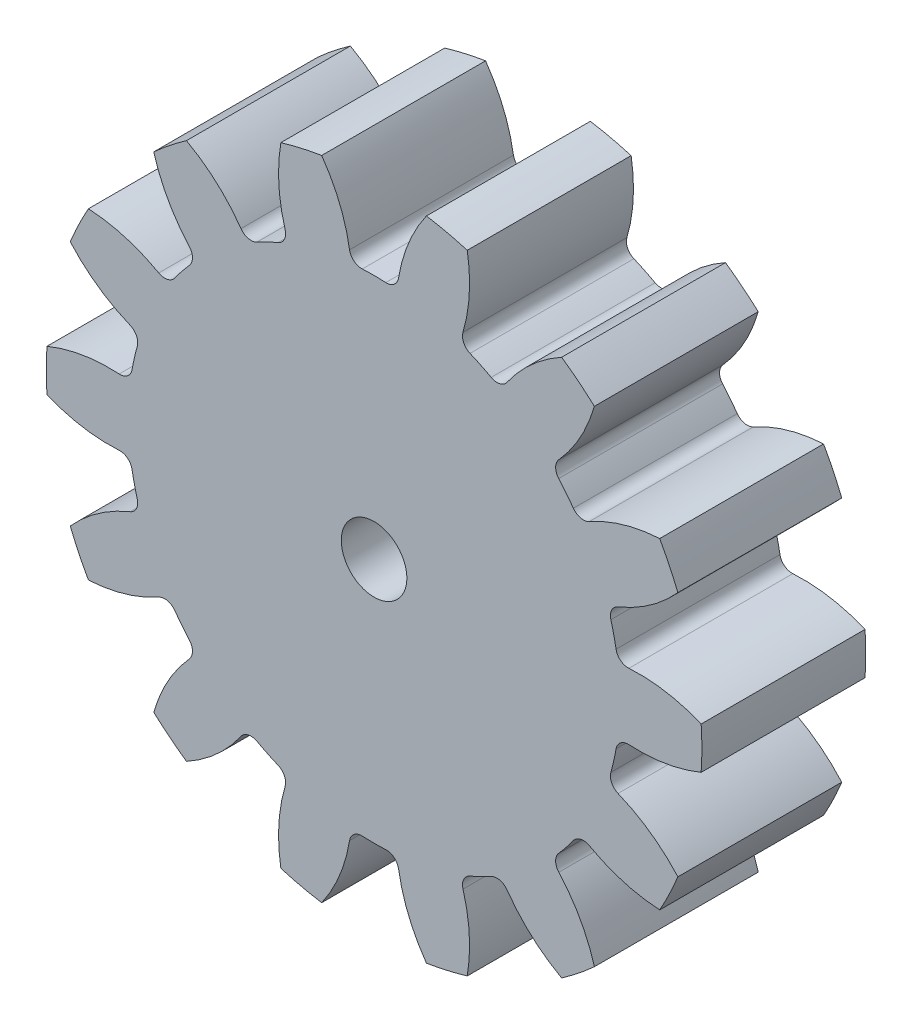
SolidWorks part; units mm, degrees
ref_plane "Front" through (0, 0, 0) normal (0, 0, 1) x (1, 0, 0)
ref_plane "Top" through (0, 0, 0) normal (0, 1, 0) x (1, 0, 0)
ref_plane "Right" through (0, 0, 0) normal (1, 0, 0) x (0, 0, -1)
sketch "Sketch1" plane through (0, 0, 0) normal (0, 0, 1) x (1, 0, 0)
  circle A0 centre (0, 0) radius 7.5
  circle A1 centre (0, 0) radius 10
  circle A2 centre (0, 0) radius 8.75
  dimension "D1" = 20
  dimension "D2" = 15
  dimension "D3" = 17.5
extrude "Boss-Extrude1" add sketch "Sketch1" along normal mid plane 5 contours A1
sketch "Sketch3" plane through (0, 0, 0) normal (0, 0, 1) x (1, 0, 0)
  line L0 (0, 0) -> (0, 10) construction
  line L1 (-0.9797, 8.695) -> (0.9797, 8.695) construction
  line L2 (-1.7667, 10.8572) -> (0, 6.0033) construction
  line L3 (0, 0) -> (2.2252, 9.7493) construction
  line L4 (0.9797, 8.695) -> (2.8899, 8.259) construction
  line L5 (0, 0) -> (-0.7032, 7.467) construction
  circle A0 centre (0, 0) radius 10 construction
  arc A1 (-2.385, 10.7383) -> (-0.7032, 7.467) centre (-5.6278, 7.0032) cw
  arc A2 (2.385, 10.7383) -> (0.7032, 7.467) centre (5.6278, 7.0032) ccw
  arc A3 (0.7032, 7.467) -> (-0.7032, 7.467) centre (0, 0) ccw
  circle A4 centre (0, 0) radius 7.5 construction
  circle A6 centre (0, 0) radius 8.75 construction
  circle A7 centre (0, 0) radius 11
  arc A8 (2.385, 10.7383) -> (-2.385, 10.7383) centre (0, 0) ccw
  circle A9 centre (0, 0) radius 10 construction
  dimension "D3" = 12.857
  dimension "D2" = 20
  dimension "D1" = 1
extrude "Cut-Extrude1" cut sketch "Sketch3" against normal through all both and the other way through all
fillet "Fillet2" radius 0.375 2 edges at (0.7032, 7.467, 0) (-0.7032, 7.467, 0)
pattern_circular "CirPattern1" count 14 over 360 about axis through (0, 0, 0) along (0, 0, 1) of "Cut-Extrude1", "Fillet2"
sketch "Sketch4" plane through (0, 0, -2.5) normal (0, 0, -1) x (-1, 0, 0)
  circle A0 centre (0, 0) radius 1
  dimension "D1" = 2
extrude "Cut-Extrude2" cut sketch "Sketch4" against normal through all
equation "\"bot_n\"= 14'bottom number of teeth"
equation "\"bot_m\"= \"bot_od\" / ( \"bot_n\" + 2 )'bottom module"
equation "\"bot_p\"= \"bot_m\" * pi'bottom pitch"
equation "\"bot_d\"= \"bot_m\" * \"bot_n\"'bottom primitive diameter"
equation "\"bot_da\"= \"bot_d\" + 2 * \"bot_m\"'bottom head diamater"
equation "\"bot_df\"= \"bot_d\" - 2 * \"bot_m\"'bottom foot diameter"
equation "\"bot_od\"= 20'bottom outer diameter"
equation "\"D1@Sketch1\"=\"bot_od\""
equation "\"D2@Sketch1\"=\"bot_df\""
equation "\"D3@Sketch1\"=\"bot_d\""
equation "\"D3@Sketch3\"= 180 / \"bot_n\""
equation "\"D1@Fillet2\"=.3*\"bot_m\""
equation "\"top_n\"= 26'top number of teeth"
equation "\"top_od\"= 38'top outer diameter"
equation "\"top_m\"= \"top_od\" / ( \"top_n\" + 2 )'top module"
equation "\"top_p\"= \"top_m\" * pi'top pitch"
equation "\"top_d\"= \"top_m\" * \"top_n\"'top primitive diameter"
equation "\"top_da\"= \"top_d\" + 2 * \"top_m\"'top head diameter"
equation "\"top_df\"= \"top_d\" - 2 * \"top_m\"'top foot diamter"
equation "\"D1@CirPattern1\"= \"bot_n\""
